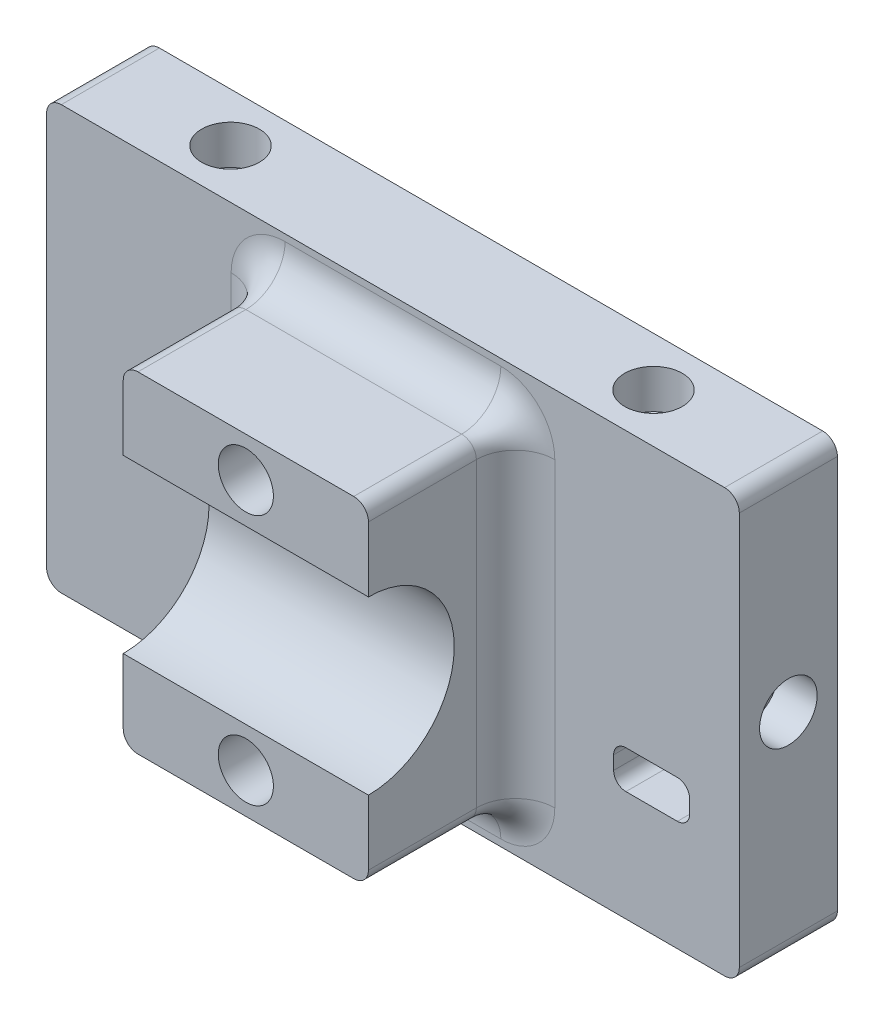
SolidWorks part; units mm, degrees
ref_plane "Plan de face" through (0, 0, 0) normal (0, 0, 1) x (1, 0, 0)
ref_plane "Plan de dessus" through (0, 0, 0) normal (0, 1, 0) x (1, 0, 0)
ref_plane "Plan de droite" through (0, 0, 0) normal (1, 0, 0) x (0, 0, -1)
sketch "Esquisse1" plane through (0, 0, 0) normal (0, 0, 1) x (1, 0, 0)
  line L1 (28.25, 17.25) -> (-28.25, 17.25)
  line L2 (28.25, 17.25) -> (28.25, -17.25)
  line L3 (28.25, -17.25) -> (-28.25, -17.25)
  line L4 (-28.25, 17.25) -> (-28.25, -17.25)
  line L5 (28.25, 17.25) -> (-28.25, -17.25) construction
  line L6 (28.25, -17.25) -> (-28.25, 17.25) construction
  point P0 (0, 0)
  dimension "D1" = 56.5
  dimension "D2" = 34.5
extrude "Base" add sketch "Esquisse1" along normal blind 8
sketch "Esquisse2" plane through (-28.25, 0, 0) normal (-1, 0, 0) x (0, 0, 1)
  line L0 (8, -17.25) -> (0, -17.25) construction
  circle A0 centre (4, 0) radius 2.35
  point P5 (4, -17.25)
  dimension "D1" = 4.7
sketch "Esquisse3" plane through (28.25, 0, 0) normal (1, 0, 0) x (0, 0, -1)
  circle A0 centre (-4, 0) radius 2.35
  circle A1 centre (-4, 0) radius 2.35 construction
extrude "Insert_M3_L" cut sketch "Esquisse2" against normal blind 3.2 contours A0
extrude "Insert_M3_R" cut sketch "Esquisse3" against normal blind 3.2
sketch "Esquisse4" plane through (0, 17.25, 0) normal (0, 1, 0) x (1, 0, 0)
  line L0 (-28.25, -8) -> (-28.25, 0) construction
  line L1 (28.25, -8) -> (28.25, 0) construction
  circle A0 centre (-17.25, -4) radius 2.35
  circle A1 centre (17.25, -4) radius 2.35
  point P9 (-28.25, -4)
  dimension "D3" = 4.7
  dimension "D1" = 11
  dimension "D2" = 11
sketch "Esquisse5" plane through (0, -17.25, -17) normal (0, 1, 0) x (1, 0, 0)
  circle A0 centre (-17.25, -21) radius 2.35
  circle A1 centre (17.25, -21) radius 2.35
  dimension "D3" = 4.7
extrude "Insert_M3_TOP" cut sketch "Esquisse4" against normal blind 3.2
extrude "Inser_M3_BOT" cut sketch "Esquisse5" along normal blind 3.2
sketch "Esquisse11" plane through (-25.05, 0, 0) normal (-1, 0, 0) x (0, 0, 1)
  circle A0 centre (4, 0) radius 1.5
  dimension "D1" = 3
extrude "Passage_Vis_L" cut sketch "Esquisse11" against normal blind 5
sketch "Esquisse12" plane through (25.05, 0, 0) normal (1, 0, 0) x (0, 0, -1)
  circle A0 centre (-4, 0) radius 1.5
  dimension "D1" = 3
extrude "Passage_Vis_R" cut sketch "Esquisse12" against normal blind 5
sketch "Esquisse10" plane through (0, 14.05, 0) normal (0, 1, 0) x (1, 0, 0)
  circle A0 centre (-17.25, -4) radius 1.5
  circle A1 centre (17.25, -4) radius 1.5
  dimension "D1" = 3
extrude "Passage_Vis_TOP" cut sketch "Esquisse10" against normal blind 5
sketch "Esquisse13" plane through (0, -14.05, 0) normal (0, -1, 0) x (1, 0, 0)
  circle A0 centre (-17.25, 4) radius 1.5
  circle A1 centre (17.25, 4) radius 1.5
  dimension "D1" = 3
extrude "Passage_Vis_BOT" cut sketch "Esquisse13" against normal blind 5
fillet "Congé1" radius 1.2 4 edges at (-28.25, -17.25, 4) (28.25, -17.25, 4) (28.25, 17.25, 4) (-28.25, 17.25, 4)
chamfer "Chanfrein1" [suppressed] distance 1 angle 45
sketch "Esquisse6" plane through (0, 0, 8) normal (0, 0, 1) x (1, 0, 0)
  line L1 (10, 13.5) -> (-10, 13.5)
  line L2 (10, 13.5) -> (10, -13.5)
  line L3 (10, -13.5) -> (-10, -13.5)
  line L4 (-10, 13.5) -> (-10, -13.5)
  line L5 (10, 13.5) -> (-10, -13.5) construction
  line L6 (10, -13.5) -> (-10, 13.5) construction
  point P0 (0, 0)
  dimension "D1" = 20
  dimension "D2" = 27
extrude "Support_Fixation" add sketch "Esquisse6" along normal blind 12
sketch "Esquisse7" plane through (-10, 0, 0) normal (-1, 0, 0) x (0, 0, 1)
  line L0 (20, 13.5) -> (20, -13.5) construction
  line L1 (20, 7) -> (20, -7)
  arc A0 (20, 7) -> (20, -7) centre (20, 0) ccw
  dimension "D1" = 7
extrude "Passage_Guidon" cut sketch "Esquisse7" against normal up to next
fillet "Congé_Vertical" radius 1.2 4 edges at (-10, 13.5, 14) (10, 13.5, 14) (10, -13.5, 14) (-10, -13.5, 14)
fillet "Congé_Base" radius 3.2 8 edges at (-9.6485, -13.1485, 8) (-10, 0, 8) (-9.6485, 13.1485, 8) (0, 13.5, 8) (9.6485, 13.1485, 8) (10, 0, 8) (9.6485, -13.1485, 8) (0, -13.5, 8)
sketch "Esquisse8" plane through (0, 0, 20) normal (0, 0, 1) x (1, 0, 0)
  line L1 (10, 7) -> (-10, 7) construction
  line L2 (11, 0) -> (-11, 0) construction
  line L3 (8.8, 13.5) -> (-8.8, 13.5) construction
  circle A0 centre (0, 10.25) radius 2.25
  circle A1 centre (0, -10.25) radius 2.25
  point P17 (0, 13.5)
  dimension "D1" = 4.5
  dimension "D2" = 3.25
extrude "Inserts_M3_Fixation" cut sketch "Esquisse8" against normal blind 3.2
chamfer "Chanfrein_Fixation" [suppressed] distance 0.4 angle 45
sketch "Esquisse9" plane through (0, 0, 16.8) normal (0, 0, 1) x (1, 0, 0)
  line L0 (11, 0) -> (-11, 0) construction
  circle A0 centre (0, 10.25) radius 1.5
  circle A1 centre (0, -10.25) radius 1.5
  dimension "D1" = 3
extrude "Passage_Vis_Fixation" cut sketch "Esquisse9" against normal blind 5
sketch "Esquisse14" plane through (0, 0, 8) normal (0, 0, 1) x (1, 0, 0)
  line L0 (-27.05, -17.25) -> (27.05, -17.25) construction
  line L1 (19, -5.15) -> (23.2, -5.15)
  line L2 (18, -6.15) -> (18, -7.25)
  line L3 (19, -8.25) -> (23.2, -8.25)
  line L4 (24.2, -6.15) -> (24.2, -7.25)
  line L5 (10, -12.3) -> (10, 12.3) construction
  arc A2 (23.2, -5.15) -> (24.2, -6.15) centre (23.2, -6.15) cw
  arc A3 (23.2, -8.25) -> (24.2, -7.25) centre (23.2, -7.25) ccw
  arc A4 (18, -7.25) -> (19, -8.25) centre (19, -7.25) ccw
  arc A5 (19, -5.15) -> (18, -6.15) centre (19, -6.15) ccw
  point P10 (24.2, -5.15)
  point P13 (24.2, -8.25)
  point P18 (18, -5.15)
  dimension "D5" = 1
  dimension "D1" = 6.2
  dimension "D2" = 3.1
  dimension "D3" = 9
  dimension "D4" = 8
extrude "Passe_Cable" cut sketch "Esquisse14" against normal blind 8 contours L4 L1 L2 L3
